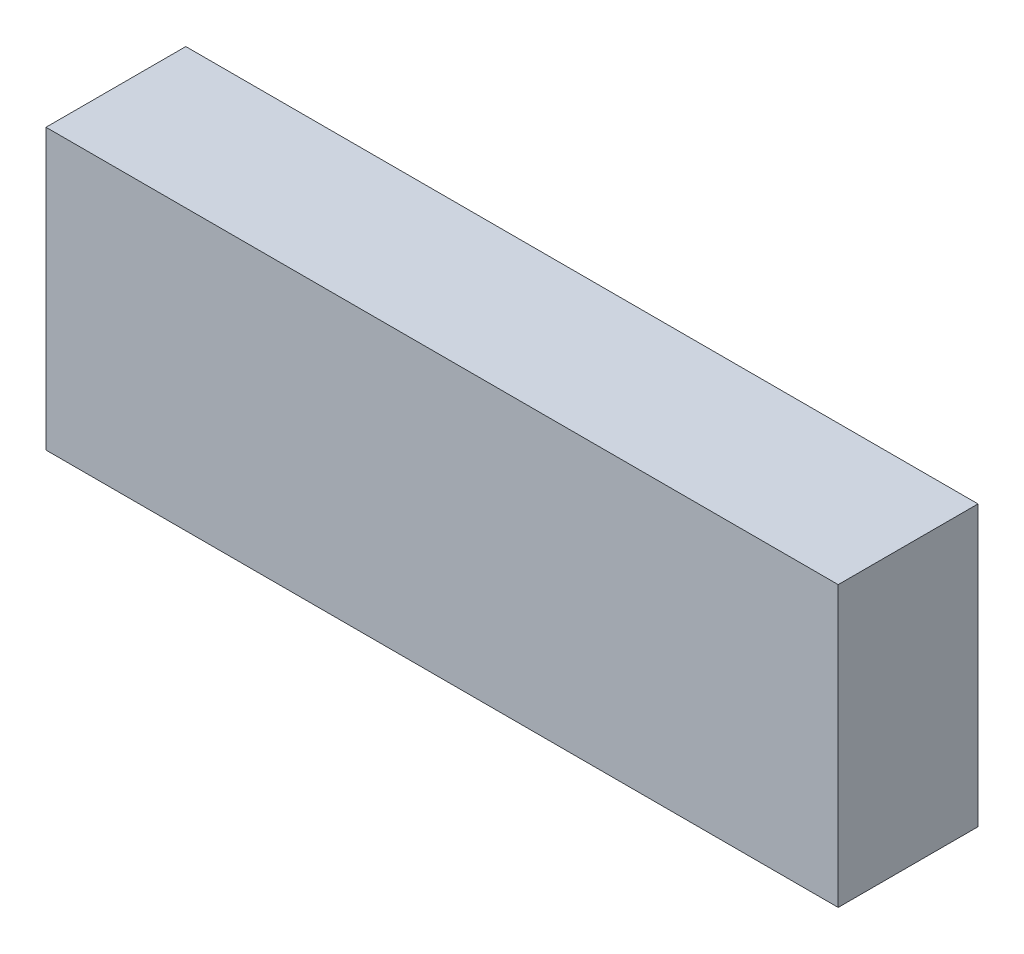
SolidWorks part; units mm, degrees
material "Pine"
ref_plane "Front Plane" through (0, 0, 0) normal (0, 0, 1) x (1, 0, 0)
ref_plane "Top Plane" through (0, 0, 0) normal (0, 1, 0) x (1, 0, 0)
ref_plane "Right Plane" through (0, 0, 0) normal (1, 0, 0) x (0, 0, -1)
sketch "Sketch1" plane through (0, 0, 0) normal (0, 0, 1) x (1, 0, 0)
  line L1 (-54.952, 25.2153) -> (52.998, 25.2153)
  line L2 (-54.952, 25.2153) -> (-54.952, -12.8847)
  line L3 (-54.952, -12.8847) -> (52.998, -12.8847)
  line L4 (52.998, 25.2153) -> (52.998, -12.8847)
  dimension "D1" = 107.95
  dimension "D2" = 38.1
extrude "Boss-Extrude2" add sketch "Sketch1" along normal blind 19.05
